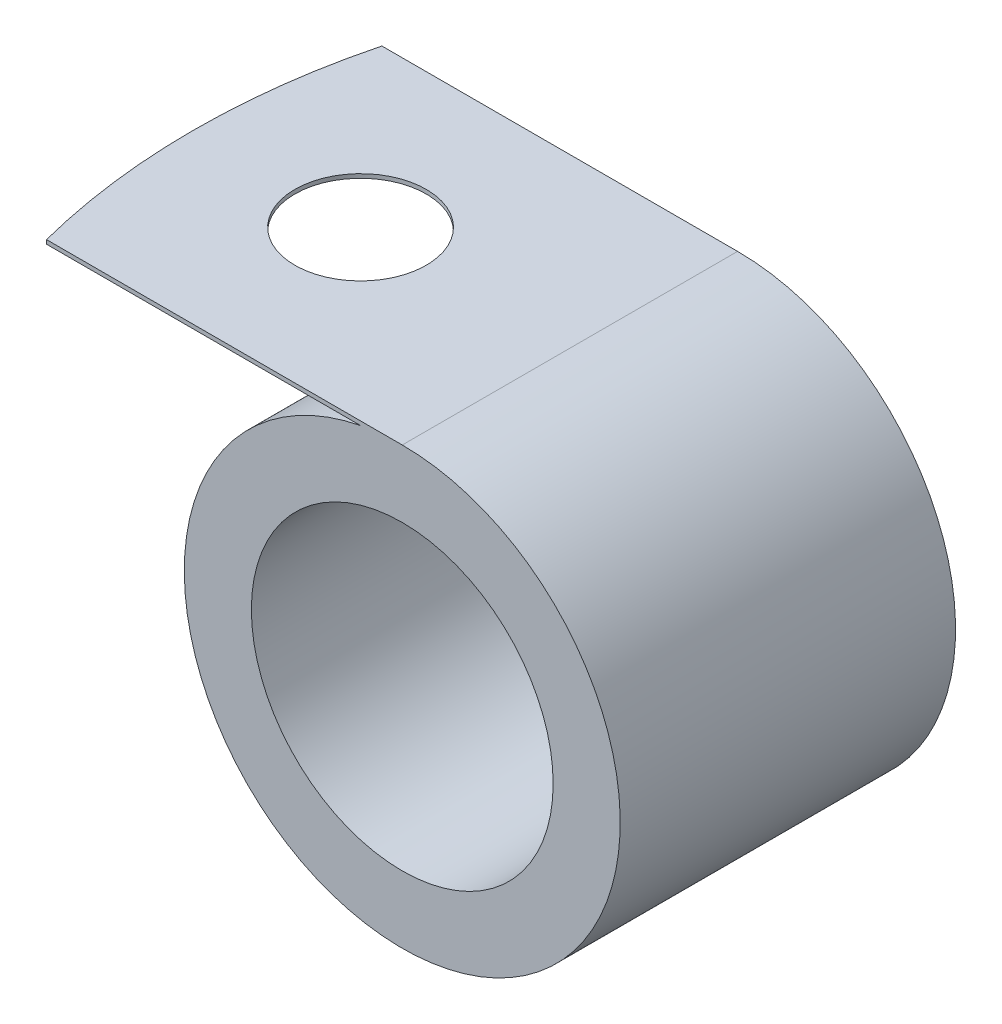
SolidWorks part; units mm, degrees
ref_plane "Front Plane" through (0, 0, 0) normal (0, 0, 1) x (1, 0, 0)
ref_plane "Top Plane" through (0, 0, 0) normal (0, 1, 0) x (1, 0, 0)
ref_plane "Right Plane" through (0, 0, 0) normal (1, 0, 0) x (0, 0, -1)
sketch "Sketch1" plane through (0, 0, 0) normal (0, 0, 1) x (1, 0, 0)
  line L0 (0, 8.255) -> (-14.2789, 8.255)
  line L1 (-14.2789, 8.255) -> (-14.2789, 8.1026)
  line L2 (-14.2789, 8.1026) -> (-1.5789, 8.1026)
  circle A0 centre (0, 0) radius 5.715
  arc A1 (-1.5789, 8.1026) -> (0, 8.255) centre (0, 0) ccw
  point P3 (-4.2148, 7.0979)
  dimension "D1" = 11.43
  dimension "D2" = 16.51
  dimension "D3" = 12.7
  dimension "D4" = 0.1524
extrude "Boss-Extrude1" add sketch "Sketch1" along normal mid plane 12.7
sketch "Sketch2" plane through (0, 8.255, 0) normal (0, 1, 0) x (1, 0, 0)
  line L0 (0, 6.35) -> (-14.2789, 6.35) construction
  line L1 (0, -6.35) -> (-14.2789, -6.35) construction
  line L2 (-14.2789, -6.35) -> (-14.2789, 6.35) construction
  line L7 (0, 6.35) -> (-14.2789, 6.35)
  line L8 (-14.2789, 6.35) -> (-14.2789, -6.35)
  line L9 (-14.2789, -6.35) -> (0, -6.35)
  line L10 (0, -6.35) -> (0, 6.35)
  line L11 (-13.4723, 6.35) -> (-14.2789, 6.35)
  line L12 (-14.2789, 6.35) -> (-14.2789, -6.35)
  line L13 (-14.2789, -6.35) -> (-13.4723, -6.35)
  arc A0 (-13.4723, 6.35) -> (-13.4723, -6.35) centre (11.1211, 0) ccw
  circle A1 centre (-7.9289, 0) radius 2.4892
  point P11 (-7.9289, -0.6078)
  line M5 (0, 6.35) -> (-14.2789, 6.35)
  line M6 (-14.2789, 6.35) -> (-14.2789, -6.35)
  line M7 (-14.2789, -6.35) -> (0, -6.35)
  dimension "D1" = 25.4
  dimension "D3" = 4.9784
  dimension "D4" = 6.35
  dimension "D2" = 0
extrude "Cut-Extrude1" cut sketch "Sketch2" against normal up to next contours A1 | A0 M5 M6 | A0 L12 M7
